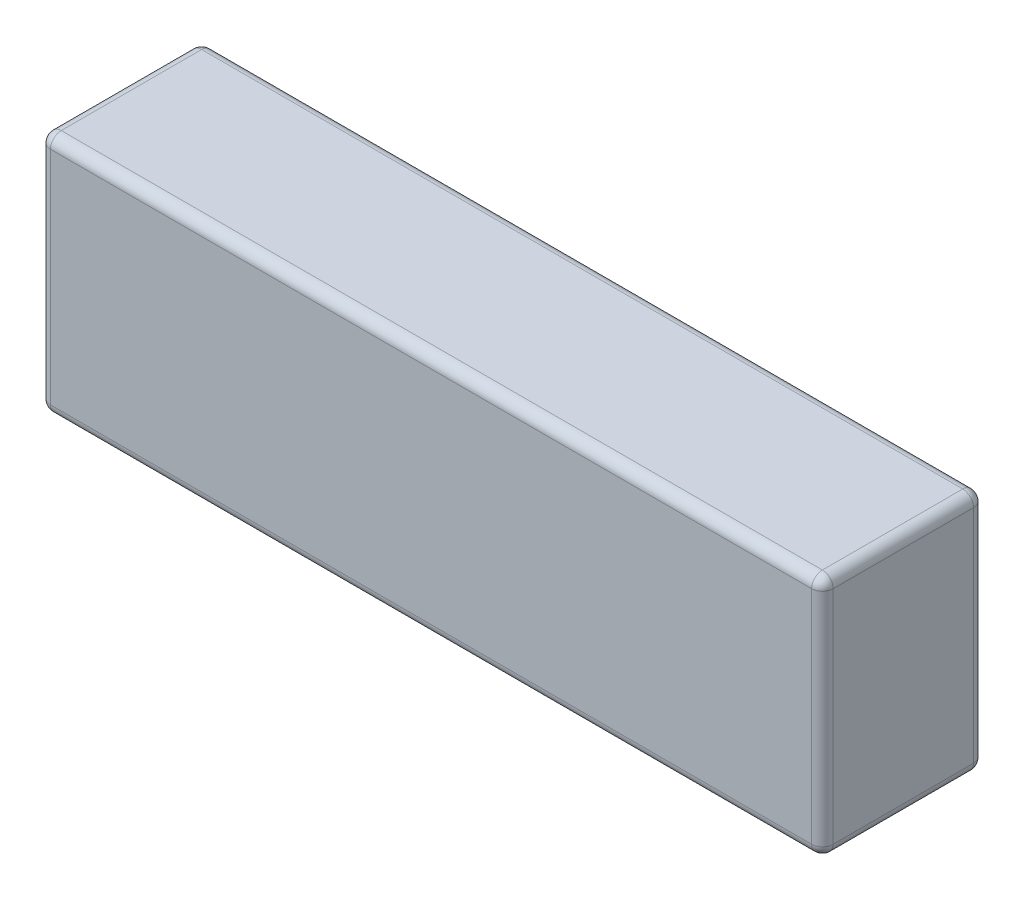
SolidWorks part; units mm, degrees
ref_plane "Front" through (0, 0, 0) normal (0, 0, 1) x (1, 0, 0)
ref_plane "Top" through (0, 0, 0) normal (0, 1, 0) x (1, 0, 0)
ref_plane "Right" through (0, 0, 0) normal (1, 0, 0) x (0, 0, -1)
sketch "Esquisse1" plane through (0, 0, 0) normal (0, 0, 1) x (1, 0, 0)
  line L1 (0, 0) -> (145, 0)
  line L2 (0, 0) -> (0, 45)
  line L3 (0, 45) -> (145, 45)
  line L4 (145, 0) -> (145, 45)
  dimension "D1" = 45
  dimension "D2" = 145
extrude "Boss.-Extru.1" add sketch "Esquisse1" along normal blind 30
fillet "Congé1" radius 2 12 edges at (0, 0, 15) (145, 0, 15) (72.5, 0, 0) (145, 22.5, 0) (0, 22.5, 0) (145, 45, 15) (0, 45, 15) (72.5, 45, 0) (72.5, 45, 30) (145, 22.5, 30) (72.5, 0, 30) (0, 22.5, 30)
